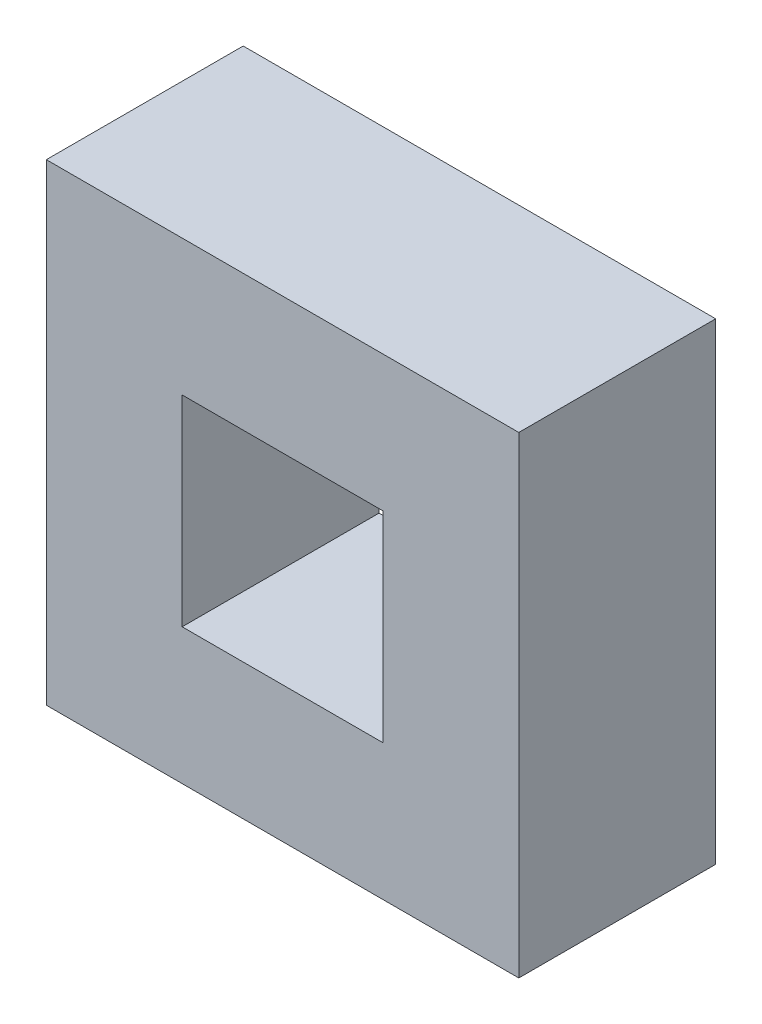
SolidWorks part; units mm, degrees
ref_plane "정면" through (0, 0, 0) normal (0, 0, 1) x (1, 0, 0)
ref_plane "윗면" through (0, 0, 0) normal (0, 1, 0) x (1, 0, 0)
ref_plane "우측면" through (0, 0, 0) normal (1, 0, 0) x (0, 0, -1)
sketch "스케치1" plane through (0, 0, 0) normal (0, 0, 1) x (1, 0, 0)
  line L0 (0, 0) -> (-58424.714, 0) construction
  line L1 (-60, 60) -> (60, 60)
  line L2 (-60, 60) -> (-60, -60)
  line L3 (-60, -60) -> (60, -60)
  line L4 (60, 60) -> (60, -60)
  line L5 (-25.5, 25.5) -> (25.5, 25.5)
  line L6 (-25.5, 25.5) -> (-25.5, -25.5)
  line L7 (-25.5, -25.5) -> (25.5, -25.5)
  line L8 (25.5, 25.5) -> (25.5, -25.5)
  line L9 (0, 0) -> (0, 58424.714) construction
  dimension "D1" = 120
  dimension "D2" = 51
  dimension "D3" = 51
  dimension "D4" = 120
  dimension "D5" = 25.5
  dimension "D6" = 25.5
  dimension "D7" = 60
  dimension "D8" = 60
extrude "보스-돌출1" add sketch "스케치1" along normal blind 50
sketch3d "URDF Reference"
  line L0 (0, 0, 0) -> (10, 0, 0) construction
  line L1 (0, 0, 0) -> (0, 0, -10) construction
  point P0 (0, 0, 0)
  point P1 (0, 0, 0)
